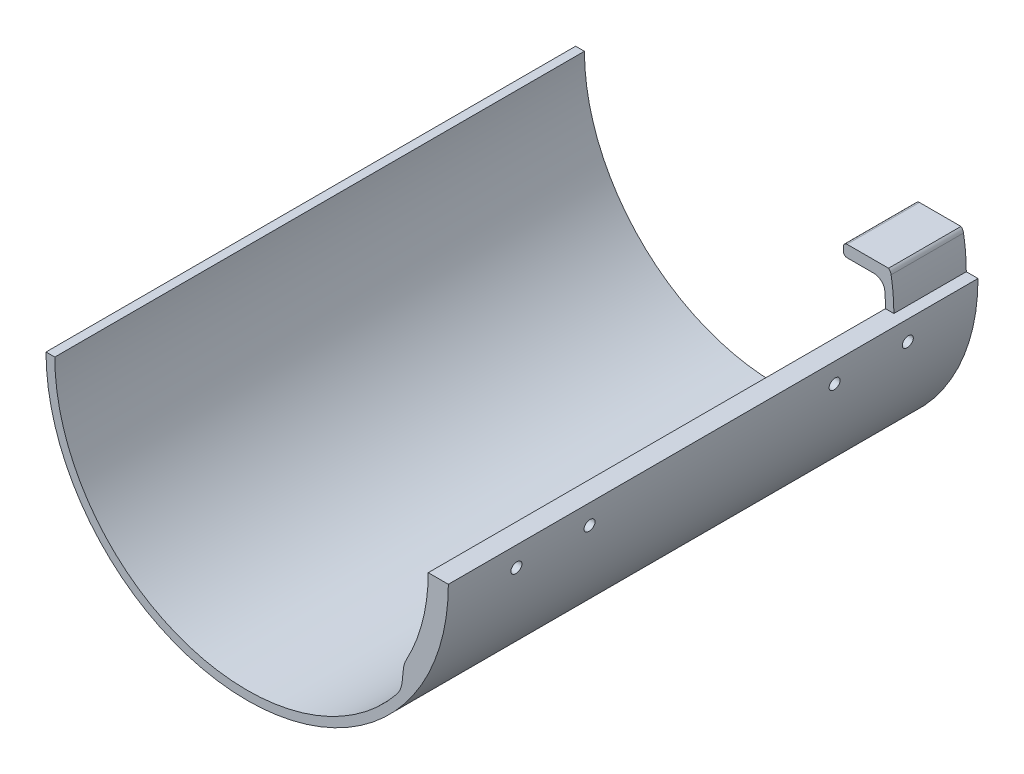
SolidWorks part; units mm, degrees
ref_plane "前视基准面" through (0, 0, 0) normal (0, 0, 1) x (1, 0, 0)
ref_plane "上视基准面" through (0, 0, 0) normal (0, 1, 0) x (1, 0, 0)
ref_plane "右视基准面" through (0, 0, 0) normal (1, 0, 0) x (0, 0, -1)
other "Configuration Table"
sketch "草图1" plane through (0, 0, 0) normal (0, 0, 1) x (1, 0, 0)
  line L0 (-55, 0) -> (-52.6, 0)
  line L1 (51.8, 0) -> (55, 0)
  line L2 (-52.6, 0) -> (51.8, 0) construction
  line L5 (42.7014, -26.2251) -> (42.3718, -29.4462)
  line L6 (0, 0) -> (0, 10) construction
  line L7 (0, 10) -> (39, 10) construction
  line L9 (38, 9) -> (38, 7.8)
  line L10 (39, 6.8) -> (46.3445, 6.8)
  line L11 (39, 10) -> (50.344, 10)
  arc A0 (-55, 0) -> (55, 0) centre (0, 0) ccw
  arc A1 (-52.6, 0) -> (40.8436, -33.1445) centre (0, 0) ccw
  arc A2 (51.0485, 8.7916) -> (51.8, 0) centre (0, 0) cw
  arc A3 (43.5118, -23.6002) -> (49.3344, 4.0452) centre (0, 0) ccw
  arc A4 (42.3718, -29.4462) -> (40.8436, -33.1445) centre (35.4082, -28.7336) cw
  arc A5 (42.7014, -26.2251) -> (43.5118, -23.6002) centre (49.665, -26.9376) cw
  arc A6 (49.3344, 4.0452) -> (46.3445, 6.8) centre (46.3445, 3.8) ccw
  arc A7 (51.0485, 8.7916) -> (50.344, 10) centre (49.0775, 8.4521) ccw
  arc A8 (39, 6.8) -> (38, 7.8) centre (39, 7.8) cw
  arc A9 (38, 9) -> (39, 10) centre (39, 9) cw
  point P16 (42.8489, -24.7835)
  point P25 (52.0183, 10)
  point P28 (38, 6.8)
  point P31 (30.5845, 10)
  dimension "D1" = 110
  dimension "D2" = 105.2
  dimension "D3" = 99
  dimension "D6" = 7
  dimension "D9" = 3
  dimension "D10" = 2
  dimension "D11" = 1
  dimension "D12" = 1
  dimension "D14" = 51.8
  dimension "D5" = 39
  dimension "D7" = 3.2
  dimension "D13" = 10
extrude "凸台-拉伸1" add sketch "草图1" along normal blind 144.8
sketch "草图4" plane through (0, 0, 144.8) normal (0, 0, 1) x (1, 0, 0)
  line L0 (55, 0) -> (0, 0)
  line L1 (0, 0) -> (50.017, 22.8758)
  arc A0 (55, 0) -> (50.017, 22.8758) centre (0, 0) ccw
sketch "草图5" plane through (0, 0, 0) normal (0, 0, -1) x (-1, 0, 0)
  line L0 (0, 0) -> (0, -5.5)
  line L1 (0, -5.5) -> (54.3615, -5.5)
  line L2 (0, 0) -> (54.3615, -5.5) construction
  line L3 (0, 0) -> (5.5, 54.3615) construction
  line L4 (0, 0) -> (0, 54.639) construction
  line L5 (0, 0) -> (-54.3615, -5.5) construction
  line L6 (0, 0) -> (-5.5, 54.3615) construction
  circle A0 centre (0, 0) radius 54.639
  dimension "D1" = 5.5
  dimension "D2" = 90
ref_plane "基准面1" through (0, 0, 0) normal (-0.9949, 0.1007, 0) x (0.1007, 0.9949, 0)
sketch "草图7" plane through (0, 0, 0) normal (-0.9949, 0.1007, 0) x (0.1007, 0.9949, 0)
  line L0 (-5.5363, -144.8) -> (-5.5363, 0) construction
  line L1 (-55, -144.8) -> (5.5363, -144.8) construction
  line L2 (-0.1363, 0) -> (-0.1363, -144.8) construction
  line L3 (54.639, 0) -> (-54.639, 0) construction
  line L4 (-5.4721, 0) -> (-10.9441, 0) construction
  circle A0 centre (-0.1363, -18.9) radius 1.5
  circle A1 centre (-0.1363, -38.9) radius 1.5
  circle A2 centre (-0.1363, -105.9) radius 1.5
  circle A3 centre (-0.1363, -125.9) radius 1.5
  dimension "D1" = 3
  dimension "D2" = 3
  dimension "D3" = 3
  dimension "D4" = 3
  dimension "D5" = 5.4
  dimension "D6" = 18.9
  dimension "D7" = 20
  dimension "D8" = 18.9
  dimension "D9" = 20
extrude "切除-拉伸6" cut sketch "草图7" against normal blind 80
sketch "草图8" plane through (0, 0, 0) normal (0, 0, -1) x (-1, 0, 0)
  line L0 (-50.017, 22.8758) -> (0, 0)
  line L1 (0, 0) -> (-55, 0)
  arc A0 (-55, 0) -> (-50.017, 22.8758) centre (0, 0) cw
  arc A1 (-50.017, 22.8758) -> (-55, 0) centre (0, 0) ccw construction
extrude "切除-拉伸8" cut sketch "草图4" against normal blind 125
